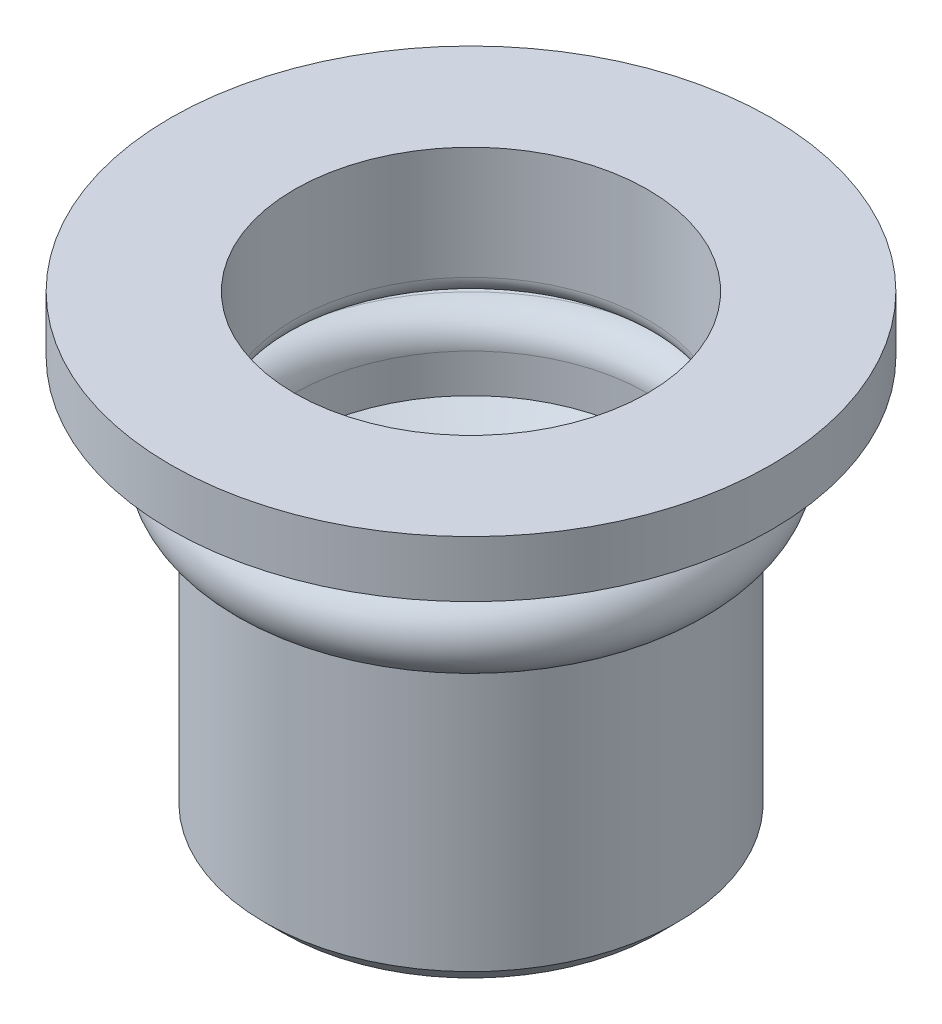
SolidWorks part; units mm, degrees
material "110 - AÇO 11SMN37 BARRA RED. - 12.70 mm"
ref_plane "Front Plane" through (0, 0, 0) normal (0, 0, 1) x (1, 0, 0)
ref_plane "Top Plane" through (0, 0, 0) normal (0, 1, 0) x (1, 0, 0)
ref_plane "Right Plane" through (0, 0, 0) normal (1, 0, 0) x (0, 0, -1)
sketch "Sketch1" plane through (0, 0, 0) normal (1, 0, 0) x (0, 0, -1)
  line L0 (4.7, 0) -> (8, 0)
  line L1 (5.5, -1.5) -> (8, -1.5)
  line L2 (5.5, -2.7) -> (5.5, -1.5)
  line L3 (5.5, -4.8832) -> (5.5, -11.8)
  line L4 (5.5, -11.8) -> (5, -12.3)
  line L5 (5, -12.3) -> (3.75, -12.3)
  line L6 (3.75, -12.3) -> (3.75, -6.3)
  line L7 (0, 0) -> (0, -11) construction
  line L8 (0, 55) -> (0, -55) construction
  line L9 (4.7, 0) -> (4.7, -3)
  line L10 (4.7, -4.7) -> (4.7, -5.7292)
  line L11 (4.7, -5.7292) -> (3.75, -6.3)
  line L12 (5.2, -3.5) -> (5.5, -3.5)
  line L13 (8, -1.5) -> (8, 0)
  arc A0 (5.5, -2.7) -> (5.6667, -4.686) centre (5.5, -3.7) cw
  arc A1 (5.5, -3.5) -> (5.5, -3.9) centre (5.5, -3.7) cw
  arc A2 (4.7, -3) -> (5.2, -3.5) centre (5.2, -3) ccw
  arc A3 (4.7, -4.7) -> (5.5, -3.9) centre (5.5, -4.7) cw
  arc A4 (5.5, -2.7) -> (5.5, -4.7) centre (5.5, -3.7) cw construction
  arc A5 (5.5, -4.8832) -> (5.6667, -4.686) centre (5.7, -4.8832) cw
  point P23 (4.7, -3.5)
  dimension "D10" = 1
  dimension "D15" = 0.5
  dimension "D16" = 0.2
  dimension "D17" = 12.3
  dimension "D1" = 16
  dimension "D2" = 1.2
  dimension "D3" = 5.5
  dimension "D4" = 7.5
  dimension "D5" = 5.5
  dimension "D6" = 2.7
  dimension "D8" = 45
  dimension "D9" = 0.5
  dimension "D11" = 0.8
  dimension "D13" = 59
  dimension "D14" = 6
  dimension "D12" = 0.8
revolve "Revolve1" add sketch "Sketch1" angle 360 about L7
cosmetic thread "Cosmetic Thread1" parameters "D2"=6
